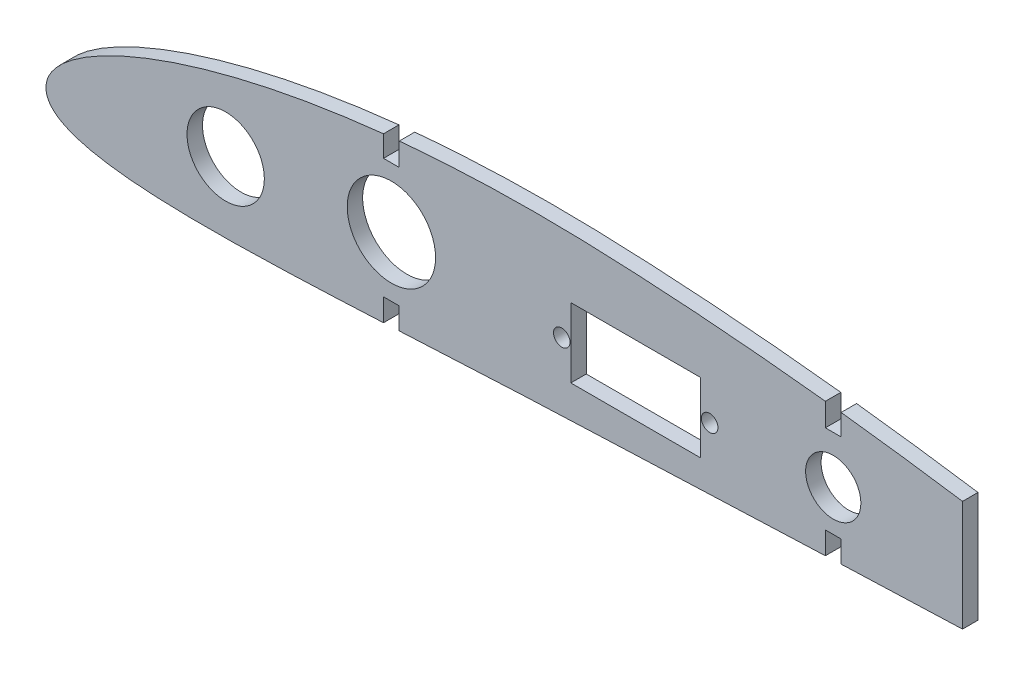
SolidWorks part; units mm, degrees
material "Фанера"
ref_plane "Front Plane" through (0, 0, 0) normal (0, 0, 1) x (1, 0, 0)
ref_plane "Top Plane" through (0, 0, 0) normal (0, 1, 0) x (1, 0, 0)
ref_plane "Right Plane" through (0, 0, 0) normal (1, 0, 0) x (0, 0, -1)
curve "Кривая5"
  spline degree 3 poles (0.048, 0.6214, 0) (0.0227, 0.3735, 0) (-0.0278, -0.1225, 0) (0.078, -0.8844, 0) (0.3497, -1.6388, 0) (0.8143, -2.3651, 0) (1.4635, -3.0393, 0) (2.291, -3.661, 0) (3.3059, -4.2358, 0) (4.5353, -4.7737, 0) (6.0297, -5.2822, 0) (7.869, -5.7653, 0) (10.1688, -6.2217, 0) (13.0754, -6.6396, 0) (16.7281, -6.993, 0) (21.19, -7.2473, 0) (26.4, -7.3766, 0) (32.1974, -7.3763, 0) (38.3978, -7.2614, 0) (44.8576, -7.0566, 0) (51.4865, -6.7865, 0) (58.231, -6.4723, 0) (65.0521, -6.1329, 0) (71.9108, -5.784, 0) (78.7714, -5.4397, 0) (85.6105, -5.111, 0) (92.4321, -4.805, 0) (99.255, -4.532, 0) (106.0974, -4.2783, 0) (112.9692, -4.0031, 0) (119.8644, -3.7232, 0) (126.7739, -3.4401, 0) (133.6816, -3.1587, 0) (140.5819, -2.8824, 0) (147.472, -2.6139, 0) (154.3526, -2.3556, 0) (161.225, -2.1094, 0) (168.0909, -1.8766, 0) (174.9516, -1.6586, 0) (181.8086, -1.4564, 0) (188.6632, -1.2704, 0) (195.5166, -1.1011, 0) (202.3695, -0.9486, 0) (209.2212, -0.8129, 0) (216.0668, -0.6936, 0) (222.8864, -0.5903, 0) (229.6176, -0.5029, 0) (236.0874, -0.4315, 0) (241.9808, -0.3765, 0) (246.559, -0.3395, 0) (249.1205, -0.3213, 0) (250, -0.315, 0) knots 0 0 0 0 0.002941 0.005884 0.009016 0.012365 0.016008 0.020037 0.024574 0.029784 0.035897 0.04324 0.052276 0.063635 0.077983 0.095698 0.11652 0.139661 0.164312 0.189919 0.216157 0.242838 0.269834 0.296993 0.324123 0.351139 0.378036 0.404946 0.431961 0.459078 0.486347 0.513641 0.540929 0.568176 0.59538 0.622543 0.649673 0.676775 0.703855 0.730919 0.757971 0.785018 0.812062 0.839103 0.866132 0.893099 0.919831 0.94581 0.969681 0.98959 1 1 1 1
curve "Кривая6"
  spline degree 3 poles (250, 0.315, 0) (249.1557, 0.545, 0) (246.7202, 1.2085, 0) (242.3913, 2.3583, 0) (236.8498, 3.7876, 0) (230.7799, 5.298, 0) (224.4559, 6.8129, 0) (218.0305, 8.2916, 0) (211.5624, 9.7197, 0) (205.0724, 11.0924, 0) (198.568, 12.4079, 0) (192.0524, 13.6653, 0) (185.5276, 14.8641, 0) (178.9953, 16.0034, 0) (172.4571, 17.0824, 0) (165.9143, 18.0998, 0) (159.3687, 19.0545, 0) (152.8218, 19.9449, 0) (146.2754, 20.7693, 0) (139.7314, 21.5257, 0) (133.1918, 22.212, 0) (126.6587, 22.8257, 0) (120.1368, 23.364, 0) (113.6286, 23.8247, 0) (107.1527, 24.2002, 0) (100.7411, 24.4984, 0) (94.4118, 24.6866, 0) (88.1559, 24.7401, 0) (81.949, 24.6588, 0) (75.7805, 24.441, 0) (69.6537, 24.0819, 0) (63.5754, 23.578, 0) (57.5552, 22.9249, 0) (51.6058, 22.1191, 0) (45.7444, 21.1566, 0) (39.9959, 20.0354, 0) (34.3979, 18.7563, 0) (29.0104, 17.3276, 0) (23.9258, 15.7719, 0) (19.2707, 14.1343, 0) (15.1791, 12.4833, 0) (11.7405, 10.8956, 0) (8.9594, 9.4296, 0) (6.7609, 8.1086, 0) (5.0337, 6.9246, 0) (3.6717, 5.8542, 0) (2.5921, 4.8713, 0) (1.7382, 3.9526, 0) (1.0699, 3.0809, 0) (0.5716, 2.2416, 0) (0.2158, 1.4308, 0) (0.1023, 0.8832, 0) (0.048, 0.6214, 0) knots 0 0 0 0 0.010162 0.029313 0.052012 0.076619 0.101948 0.127526 0.153184 0.178868 0.204558 0.230246 0.255926 0.281594 0.307246 0.332878 0.358485 0.384061 0.409603 0.435104 0.460559 0.485959 0.511303 0.536552 0.561723 0.586629 0.611085 0.635251 0.659272 0.683164 0.706922 0.730536 0.753983 0.777235 0.800246 0.822951 0.845237 0.866916 0.887662 0.906968 0.924203 0.938879 0.950932 0.960693 0.968647 0.975233 0.980795 0.985584 0.989782 0.993521 0.996902 1 1 1 1
sketch "Эскиз1" plane through (0, 0, 0) normal (0, 0, 1) x (1, 0, 0)
  line L0 (250.1305, 0) -> (250.1305, 54.8427) construction
  line L1 (0, 0) -> (0, 70.5199) construction
  line L2 (0, 0) -> (253.0634, 0) construction
  line L3 (62.5326, 62.6361) -> (62.5326, -41.5636) construction
  line L4 (142.5326, 67.9319) -> (142.5326, 25.1988) construction
  line L5 (175.0913, 63.8571) -> (175.0913, -32.3947) construction
  line L6 (32.5326, -14.3434) -> (32.5326, 29.5903) construction
  line L7 (142.5326, 21.1988) -> (142.5326, -57.0034) construction
  line L8 (61.1076, 19.4501) -> (63.9576, 19.4501)
  line L9 (61.1076, 19.4501) -> (61.1076, 23.3031)
  line L11 (63.9576, 19.4501) -> (63.9576, 23.5885)
  line L12 (61.1076, 19.4501) -> (62.5326, 23.4501) construction
  line L13 (62.5326, 23.4501) -> (63.9576, 19.4501) construction
  line L15 (61.1076, -6.3284) -> (61.1076, -2.2577)
  line L16 (61.1076, -2.2577) -> (63.9576, -2.2577)
  line L17 (63.9576, -6.1866) -> (63.9576, -2.2577)
  line L18 (62.5326, -6.2577) -> (63.9576, -2.2577) construction
  line L19 (61.1076, -2.2577) -> (62.5326, -6.2577) construction
  line L20 (141.1076, 17.1988) -> (143.9576, 17.1988)
  line L21 (141.1076, 17.1988) -> (141.1076, 21.3608)
  line L23 (143.9576, 17.1988) -> (143.9576, 21.0336)
  line L24 (141.1076, 17.1988) -> (142.5326, 21.1988) construction
  line L25 (142.5326, 21.1988) -> (143.9576, 17.1988) construction
  line L26 (165.9405, 18.0854) -> (165.9405, -1.9504)
  line L28 (141.1076, -2.8629) -> (141.1076, 1.1931)
  line L29 (141.1076, 1.1931) -> (143.9576, 1.1931)
  line L30 (143.9576, -2.7512) -> (143.9576, 1.1931)
  line L31 (142.5326, -2.8069) -> (143.9576, 1.1931) construction
  line L32 (141.1076, 1.1931) -> (142.5326, -2.8069) construction
  line L33 (118.5181, 13.7939) -> (121.7881, 13.7939) construction
  line L34 (95.0181, 1.1939) -> (118.5181, 1.1939)
  line L35 (95.0181, 1.1939) -> (95.0181, 13.7939)
  line L36 (95.0181, 13.7939) -> (118.5181, 13.7939)
  line L37 (118.5181, 1.1939) -> (118.5181, 13.7939)
  line L38 (95.0181, 1.1939) -> (118.5181, 13.7939) construction
  line L39 (95.0181, 13.7939) -> (118.5181, 1.1939) construction
  line L40 (121.7881, 13.7939) -> (121.7881, 1.1939) construction
  line L41 (121.7881, 1.1939) -> (118.5181, 1.1939) construction
  line L42 (106.7681, 19.4501) -> (106.7681, -1.9504) construction
  line L43 (91.7481, 1.1939) -> (95.0181, 1.1939) construction
  line L44 (95.0181, 13.7939) -> (91.7481, 13.7939) construction
  line L45 (91.7481, 13.7939) -> (91.7481, 1.1939) construction
  arc A0 (250, 0.315) -> (250, -0.315) centre (249.685, 0) cw
  circle A1 centre (62.5326, 8.5962) radius 8
  circle A2 centre (142.5326, 8.5962) radius 5
  circle A3 centre (32.5326, 5.4481) radius 7
  arc A6 (175.0913, 16.6448) -> (175.0913, -1.657) centre (175.0913, 7.4939) ccw
  circle A7 centre (120.1531, 7.4939) radius 1.5
  circle A8 centre (93.3831, 7.4939) radius 1.5
  spline S2 degree 3 poles (0.048, 0.6214) (0.0227, 0.3735) (-0.0278, -0.1225) (0.078, -0.8844) (0.3497, -1.6388) (0.8143, -2.3651) (1.4635, -3.0393) (2.291, -3.661) (3.3059, -4.2358) (4.5353, -4.7737) (6.0297, -5.2822) (7.869, -5.7653) (10.1688, -6.2217) (13.0754, -6.6396) (16.7281, -6.993) (21.19, -7.2473) (26.4, -7.3766) (32.1974, -7.3763) (38.3978, -7.2614) (44.8576, -7.0566) (51.4865, -6.7865) (56.9206, -6.5334) (60.1398, -6.3761) (61.1076, -6.3284) knots 0 0 0 0 0.002941 0.005884 0.009016 0.012365 0.016008 0.020037 0.024574 0.029784 0.035897 0.04324 0.052276 0.063635 0.077983 0.095698 0.11652 0.139661 0.164312 0.189919 0.216157 0.242838 0.254307 0.254307 0.254307 0.254307
  spline S3 degree 3 poles (250, 0.315) (249.1557, 0.545) (246.7202, 1.2085) (242.3913, 2.3583) (236.8498, 3.7876) (230.7799, 5.298) (224.4559, 6.8129) (218.0305, 8.2916) (211.5624, 9.7197) (205.0724, 11.0924) (198.568, 12.4079) (192.0524, 13.6653) (185.5276, 14.8641) (178.9953, 16.0034) (172.4571, 17.0824) (165.9143, 18.0998) (159.3687, 19.0545) (152.8218, 19.9449) (147.6839, 20.5919) (144.7288, 20.9433) (143.9576, 21.0336) knots 0 0 0 0 0.010162 0.029313 0.052012 0.076619 0.101948 0.127526 0.153184 0.178868 0.204558 0.230246 0.255926 0.281594 0.307246 0.332878 0.358485 0.384061 0.409603 0.418619 0.418619 0.418619 0.418619
  spline S4 degree 3 poles (61.1076, 23.3031) (59.9179, 23.1768) (56.7397, 22.8145) (51.6058, 22.1191) (45.7444, 21.1566) (39.9959, 20.0354) (34.3979, 18.7563) (29.0104, 17.3276) (23.9258, 15.7719) (19.2707, 14.1343) (15.1791, 12.4833) (11.7405, 10.8956) (8.9594, 9.4296) (6.7609, 8.1086) (5.0337, 6.9246) (3.6717, 5.8542) (2.5921, 4.8713) (1.7382, 3.9526) (1.0699, 3.0809) (0.5716, 2.2416) (0.2158, 1.4308) (0.1023, 0.8832) (0.048, 0.6214) knots 0.740091 0.740091 0.740091 0.740091 0.753983 0.777235 0.800246 0.822951 0.845237 0.866916 0.887662 0.906968 0.924203 0.938879 0.950932 0.960693 0.968647 0.975233 0.980795 0.985584 0.989782 0.993521 0.996902 1 1 1 1
  spline S5 degree 3 poles (63.9576, -6.1866) (64.3178, -6.1685) (66.9697, -6.0353) (71.9108, -5.784) (78.7714, -5.4397) (85.6105, -5.111) (92.4321, -4.805) (99.255, -4.532) (106.0974, -4.2783) (112.9692, -4.0031) (119.8644, -3.7232) (126.7739, -3.4401) (133.8556, -3.1516) (138.6334, -2.9604) (141.1076, -2.8629) knots 0.265565 0.265565 0.265565 0.265565 0.269834 0.296993 0.324123 0.351139 0.378036 0.404946 0.431961 0.459078 0.486347 0.513641 0.540929 0.570237 0.570237 0.570237 0.570237
  spline S6 degree 3 poles (143.9576, -2.7512) (145.1302, -2.7056) (148.5961, -2.5717) (154.3526, -2.3556) (161.225, -2.1094) (168.0909, -1.8766) (174.9516, -1.6586) (181.8086, -1.4564) (188.6632, -1.2704) (195.5166, -1.1011) (202.3695, -0.9486) (211.4992, -0.7677) (220.6031, -0.6199) (229.6176, -0.5029) (236.0874, -0.4315) (241.9808, -0.3765) (246.559, -0.3395) (249.1205, -0.3213) (250, -0.315) knots 0.58149 0.58149 0.58149 0.58149 0.59538 0.622543 0.649673 0.676775 0.703855 0.730919 0.757971 0.785018 0.812062 0.839103 0.893099 0.919831 0.94581 0.969681 0.98959 1 1 1 1
  spline S7 degree 3 poles (141.1076, 21.3608) (140.6472, 21.4126) (138.0081, 21.7065) (133.1918, 22.212) (126.6587, 22.8257) (120.1368, 23.364) (113.6286, 23.8247) (107.1527, 24.2002) (100.7411, 24.4984) (94.4118, 24.6866) (88.1559, 24.7401) (81.949, 24.6588) (75.7805, 24.441) (69.7854, 24.0896) (65.8508, 23.7665) (63.9576, 23.5885) knots 0.429724 0.429724 0.429724 0.429724 0.435104 0.460559 0.485959 0.511303 0.536552 0.561723 0.586629 0.611085 0.635251 0.659272 0.683164 0.706922 0.729004 0.729004 0.729004 0.729004
  point P20 (106.7681, 7.4939)
  point P22 (62.5326, 23.4501)
  point P23 (62.5326, -6.2577)
  point P26 (32.5326, 18.2506)
  point P27 (32.5326, -7.3543)
  point P30 (62.5326, 23.4501)
  point P31 (62.5326, -6.2577)
  point P40 (142.5326, 21.1988)
  point P43 (142.5326, -2.8069)
  point P53 (175.0913, 16.6448)
  point P56 (175.0913, -1.657)
  point P70 (120.1531, 13.7939)
  dimension "D3" = 16
  dimension "D8" = 14
  dimension "D10" = 10
  dimension "D27" = 9.1509
  dimension "D28" = 3
  dimension "D1" = 250.1305
  dimension "D2" = 62.5326
  dimension "D4" = 80
  dimension "D5" = 75.0391
  dimension "D6" = 29.7079
  dimension "D7" = 14.8539
  dimension "D12" = 30
  dimension "D13" = 25.6049
  dimension "D14" = 12.8025
  dimension "D15" = 2.85
  dimension "D16" = 4
  dimension "D17" = 1.425
  dimension "D18" = 2.85
  dimension "D19" = 4
  dimension "D20" = 1.425
  dimension "D21" = 2.85
  dimension "D22" = 4
  dimension "D23" = 1.425
  dimension "D24" = 2.85
  dimension "D25" = 4
  dimension "D26" = 1.425
  dimension "D9" = 12.6
  dimension "D11" = 23.5
  dimension "D29" = 3.27
extrude "Бобышка-Вытянуть1" add sketch "Эскиз1" along normal mid plane 2.8 contours L21 S7 L11 L8 L9 S4 S2 L15 L16 L17 S5 L28 L29 L30 S6 L26 S3 L23 L20 A1 A2 A3 L35
equation "\"D2@Эскиз1\"=\"D1@Эскиз1\"/4"
equation "\"D7@Эскиз1\"=\"D6@Эскиз1\"/2"
equation "\"D5@Эскиз1\"=\"D1@Эскиз1\"*0.3"
equation "\"D14@Эскиз1\"=\"D13@Эскиз1\"/2"
equation "\"t\"= 2.85"
equation "\"D17@Эскиз1\"=\"D15@Эскиз1\"/2"
equation "\"D18@Эскиз1\"=\"t\""
equation "\"D20@Эскиз1\"=\"D18@Эскиз1\"/2"
equation "\"D21@Эскиз1\"=\"t\""
equation "\"D23@Эскиз1\"=\"D21@Эскиз1\"/2"
equation "\"D24@Эскиз1\"=\"t\""
equation "\"D26@Эскиз1\"=\"D24@Эскиз1\"/2"
